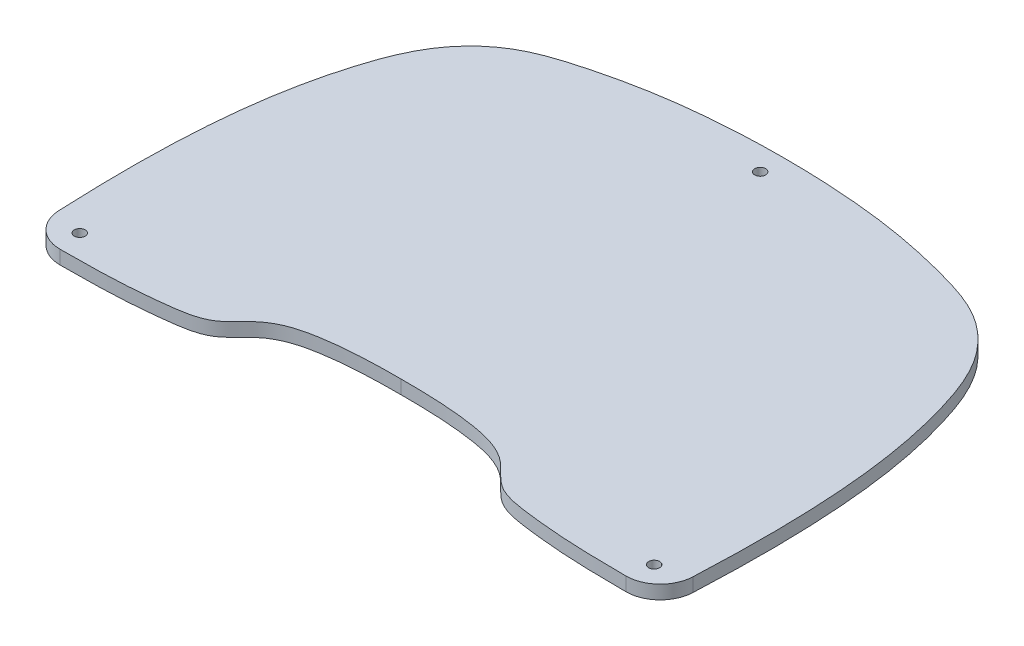
SolidWorks part; units mm, degrees
ref_plane "Front Plane" through (0, 0, 0) normal (0, 0, 1) x (1, 0, 0)
ref_plane "Top Plane" through (0, 0, 0) normal (0, 1, 0) x (1, 0, 0)
ref_plane "Right Plane" through (0, 0, 0) normal (1, 0, 0) x (0, 0, -1)
sketch "Sketch1" plane through (0, 0, 0) normal (0, 1, 0) x (1, 0, 0)
  line L1 (-120, 155) -> (120, 155)
  line L2 (-120, 155) -> (-120, -155)
  line L3 (-120, -155) -> (120, -155)
  line L4 (120, 155) -> (120, -155)
  point P4 (0, 155)
  point P6 (-120, 0)
  dimension "D1" = 240
  dimension "D2" = 310
extrude "Boss-Extrude1" add sketch "Sketch1" along normal blind 4 contours L2 L1 L4 L3
sketch "Sketch2" plane through (0, 4, 0) normal (0, 1, 0) x (1, 0, 0)
  line L0 (-120, 155) -> (120, 155) construction
  line L1 (-120, 0) -> (120, 0)
  line L2 (-120, 155) -> (-120, -155) construction
  circle B0 centre (49, -30) radius 1.75
  circle B1 centre (-49, -30) radius 1.75
  circle B2 centre (-88.957, -132.3382) radius 1.75
  circle B3 centre (0, -146) radius 1.75
  circle B4 centre (88.957, -132.3382) radius 1.75
  circle B5 centre (110.4185, 44.9345) radius 1.75
  circle B6 centre (88.957, 132.3382) radius 1.75
  circle B7 centre (0, 146) radius 1.75
  circle B8 centre (-88.957, 132.3382) radius 1.75
  circle B9 centre (-110.4185, 44.9345) radius 1.75
  spline B10 degree 3 poles (0, 155) (30.5722, 155) (80.3433, 153.7333) (119.2212, 117.6544) (120, 45.41) (120, 0) knots 0 0 0 0 0.458017 0.558017 1 1 1 1
  spline B11 degree 3 poles (0, 155) (-30.5722, 155) (-80.3433, 153.7333) (-119.2212, 117.6544) (-120, 45.41) (-120, 0) knots 0 0 0 0 0.458017 0.558017 1 1 1 1
  spline B12 degree 3 poles (0, -155) (30.5722, -155) (80.3433, -153.7333) (119.2212, -117.6544) (120, -45.41) (120, 0) knots 0 0 0 0 0.458017 0.558017 1 1 1 1
  spline B13 degree 3 poles (0, -155) (-30.5722, -155) (-80.3433, -153.7333) (-119.2212, -117.6544) (-120, -45.41) (-120, 0) knots 0 0 0 0 0.458017 0.558017 1 1 1 1
  line M2 (-120, -155) -> (120, -155)
  line M3 (120, -155) -> (120, 155)
  line M4 (120, 155) -> (-120, 155)
  line M5 (-120, 155) -> (-120, -155)
sketch_block_instance "Base-2-F1-1"
sketch_block "Base-2-F1"
extrude "Cut-Extrude1" cut sketch "Sketch2" against normal up to next contours B11 M4 M5 | B10 M4 M3 | B12 M2 M3 | B13 M2 M5 | B8 | B7 | B6 | B9 | B1 | B0 | B2 | B3 | B4 | B5
sketch "Sketch3" plane through (0, 4, 0) normal (0, 1, 0) x (1, 0, 0)
  line L1 (-120, 0) -> (120, 0)
  line L2 (-120, 0) -> (-120, -155)
  line L3 (-120, -155) -> (120, -155)
  line L4 (120, 0) -> (120, -155)
  line L5 (-120, 0) -> (120, 0)
  line L6 (-120, 0) -> (-120, 5)
  line L7 (-120, 5) -> (120, 5)
  line L8 (120, 0) -> (120, 5)
  point P9 (0, 5)
  circle M6 centre (88.957, -132.3382) radius 1.75
  circle M7 centre (0, -146) radius 1.75
  circle M11 centre (-49, -30) radius 1.75
  circle M12 centre (49, -30) radius 1.75
  circle M13 centre (-88.957, -132.3382) radius 1.75
  spline M15 degree 3 poles (0, 155) (-30.5722, 155) (-80.3433, 153.7333) (-119.2212, 117.6544) (-120, 45.41) (-120, 0) knots 0 0 0 0 0.458017 0.558017 1 1 1 1
  spline M16 degree 3 poles (-120, 0) (-120, -45.41) (-119.2212, -117.6544) (-80.3433, -153.7333) (-30.5722, -155) (0, -155) knots 0 0 0 0 0.441983 0.541983 1 1 1 1
  spline M17 degree 3 poles (0, -155) (30.5722, -155) (80.3433, -153.7333) (119.2212, -117.6544) (120, -45.41) (120, 0) knots 0 0 0 0 0.458017 0.558017 1 1 1 1
  spline M18 degree 3 poles (120, 0) (120, 45.41) (119.2212, 117.6544) (80.3433, 153.7333) (30.5722, 155) (0, 155) knots 0 0 0 0 0.441983 0.541983 1 1 1 1
  dimension "D1" = 155
  dimension "D2" = 5
extrude "Cut-Extrude2" cut sketch "Sketch3" against normal up to next contours L1 M16 M17 M6 M12 M13 M11 M7 | L7 L1 M15 M18
fillet "Fillet3" radius 3 2 edges
sketch "Sketch4" plane through (0, 4, 0) normal (0, 1, 0) x (1, 0, 0)
  line L0 (0, 5) -> (0, 144.25) construction
  line L1 (-54.5, 120.415) -> (-54.5, 27.625) construction
  line L2 (-57.5, 24.625) -> (-86.789, 24.625) construction
  line L3 (54.5, 120.415) -> (54.5, 27.625) construction
  line L4 (57.5, 24.625) -> (86.789, 24.625) construction
  line L5 (-116.9911, 5) -> (116.9911, 5) construction
  line L7 (-116.9911, 5) -> (116.9911, 5)
  circle A0 centre (0, 146) radius 1.75 construction
  arc A1 (-54.5, 120.415) -> (-58.1637, 123.3407) centre (-57.5, 120.415) ccw construction
  arc A2 (-54.5, 27.625) -> (-57.5, 24.625) centre (-57.5, 27.625) cw construction
  arc A3 (-86.789, 24.625) -> (-89.7877, 27.5373) centre (-86.789, 27.625) cw construction
  arc A4 (54.5, 120.415) -> (58.1637, 123.3407) centre (57.5, 120.415) cw
  arc A5 (86.789, 24.625) -> (89.7877, 27.5373) centre (86.789, 27.625) ccw construction
  arc A6 (54.5, 27.625) -> (57.5, 24.625) centre (57.5, 27.625) ccw construction
  circle A8 centre (0, 132) radius 1.6
  arc A10 (-119.9911, 8.0075) -> (-116.9911, 5) centre (-116.9911, 8) ccw construction
  arc A11 (116.9911, 5) -> (119.9911, 8.0075) centre (116.9911, 8) ccw construction
  arc A12 (-119.9911, 8.0075) -> (-116.9911, 5) centre (-116.9911, 8) ccw
  arc A13 (116.9911, 5) -> (119.9911, 8.0075) centre (116.9911, 8) ccw
  spline S0 degree 3 poles (-58.1637, 123.3407) (-67.2409, 121.2816) (-77.0217, 114.715) (-85.2116, 91.8938) (-89.0656, 63.3647) (-90.1983, 41.5749) (-89.7877, 27.5373) knots 0.021021 0.021021 0.021021 0.021021 0.204024 0.379971 0.619261 0.974387 0.974387 0.974387 0.974387 construction
  spline S1 degree 3 poles (58.1637, 123.3407) (67.2409, 121.2816) (77.0217, 114.715) (85.2116, 91.8938) (89.0656, 63.3647) (90.1983, 41.5749) (89.7877, 27.5373) knots 0.021021 0.021021 0.021021 0.021021 0.204024 0.379971 0.619261 0.974387 0.974387 0.974387 0.974387 construction
  spline S2 degree 3 poles (2832.9104, 1141.6728) (-715.0695, -90.7684) (0.5711, 227.7625) (185.9079, 55.7686) (-78.3221, -939.6313) (842.9767, 2919.0484) knots -2.051868 -2.051868 -2.051868 -2.051868 0.458017 0.558017 2.715289 2.715289 2.715289 2.715289 only from (0, 155) to (119.9911, 8.0075) construction
  spline S3 degree 3 poles (-2832.9104, 1141.6728) (715.0695, -90.7684) (-0.5711, 227.7625) (-185.9079, 55.7686) (78.3221, -939.6313) (-842.9767, 2919.0484) knots -2.051868 -2.051868 -2.051868 -2.051868 0.458017 0.558017 2.715289 2.715289 2.715289 2.715289 only from (0, 155) to (-119.9911, 8.0075) construction
  spline S4 degree 3 poles (0, 155) (30.5722, 155) (80.3433, 153.7333) (118.2271, 118.5769) (119.8813, 52.1095) (119.9911, 8.0075) knots 0 0 0 0 0.458017 0.558017 0.97443 0.97443 0.97443 0.97443
  spline S5 degree 3 poles (0, 155) (-30.5722, 155) (-80.3433, 153.7333) (-118.2271, 118.5769) (-119.8813, 52.1095) (-119.9911, 8.0075) knots 0 0 0 0 0.458017 0.558017 0.97443 0.97443 0.97443 0.97443
  spline S6 degree 3 poles (-92.2335, 10) (-93.109, 24.4617) (-94.1413, 55.9294) (-89.8488, 89.0425) (-82.7766, 109.2192) (-77.5058, 118.8792) (-67.5607, 127.9642) (-51.2025, 133.2045) (-28.9563, 138.0005) (-10.5009, 139) (0, 139) knots 0.048683 0.048683 0.048683 0.048683 0.273512 0.499349 0.541604 0.589205 0.661189 0.734095 0.840041 1 1 1 1
  spline S7 degree 3 poles (-92.2335, 10) (-80.6643, 10) (-67.3798, 9.833) (-50.8213, 11.7564) (-41.6876, 13.0928) (-34.6105, 23.0328) (-19.1579, 26.7733) (-6.7173, 27) (0, 27) knots 0 0 0 0 0.354855 0.417369 0.52509 0.626101 0.77445 1 1 1 1
  spline S8 degree 3 poles (92.2335, 10) (93.109, 24.4617) (94.1413, 55.9294) (89.8488, 89.0425) (82.7766, 109.2192) (77.5058, 118.8792) (67.5607, 127.9642) (51.2025, 133.2045) (28.9563, 138.0005) (10.5009, 139) (0, 139) knots 0.048683 0.048683 0.048683 0.048683 0.273512 0.499349 0.541604 0.589205 0.661189 0.734095 0.840041 1 1 1 1
  spline S9 degree 3 poles (92.2335, 10) (80.6643, 10) (67.3798, 9.833) (50.8213, 11.7564) (41.6876, 13.0928) (34.6105, 23.0328) (19.1579, 26.7733) (6.7173, 27) (0, 27) knots 0 0 0 0 0.354855 0.417369 0.52509 0.626101 0.77445 1 1 1 1
  point P0 (0, 24.625)
  point P5 (39.5, 74.625)
  point P6 (0, 74.625)
  point P21 (-54.5, 24.625)
  point P39 (0, 146)
  line B0 (-39.5, 124.625) -> (39.5, 124.625) construction
  line B1 (-39.5, 124.625) -> (-39.5, 24.625) construction
  line B2 (-39.5, 24.625) -> (39.5, 24.625) construction
  line B3 (39.5, 124.625) -> (39.5, 24.625) construction
  circle B4 centre (35.5, 120.625) radius 1.35
  circle B5 centre (-22.5, 120.625) radius 1.35
  circle B6 centre (-22.5, 34.625) radius 1.35
  circle B7 centre (35.5, 34.625) radius 1.35
  dimension "D3" = 3
  dimension "D2" = 3.2
  dimension "D1" = 15
  dimension "D4" = 14
  dimension "D5" = 5
  dimension "D6" = 22
sketch_block_instance "JETSON-NANO-1"
sketch_block "JETSON-NANO"
extrude "Cut-Extrude3" cut sketch "Sketch4" against normal blind 5
fillet "Fillet4" radius 10 2 edges at (92.2335, 2, -10) (-92.2335, 2, -10)
sketch "Sketch5" plane through (0, 4, 0) normal (0, 1, 0) x (1, 0, 0)
  line L0 (0, 132) -> (0, 17) construction
  line L1 (-84, 17) -> (84, 17) construction
  circle A0 centre (-84, 17) radius 1.6
  circle A1 centre (84, 17) radius 1.6
  point P6 (0, 17)
  dimension "D1" = 3.2
  dimension "D2" = 17
  dimension "D3" = 168
extrude "Cut-Extrude4" cut sketch "Sketch5" against normal through all
